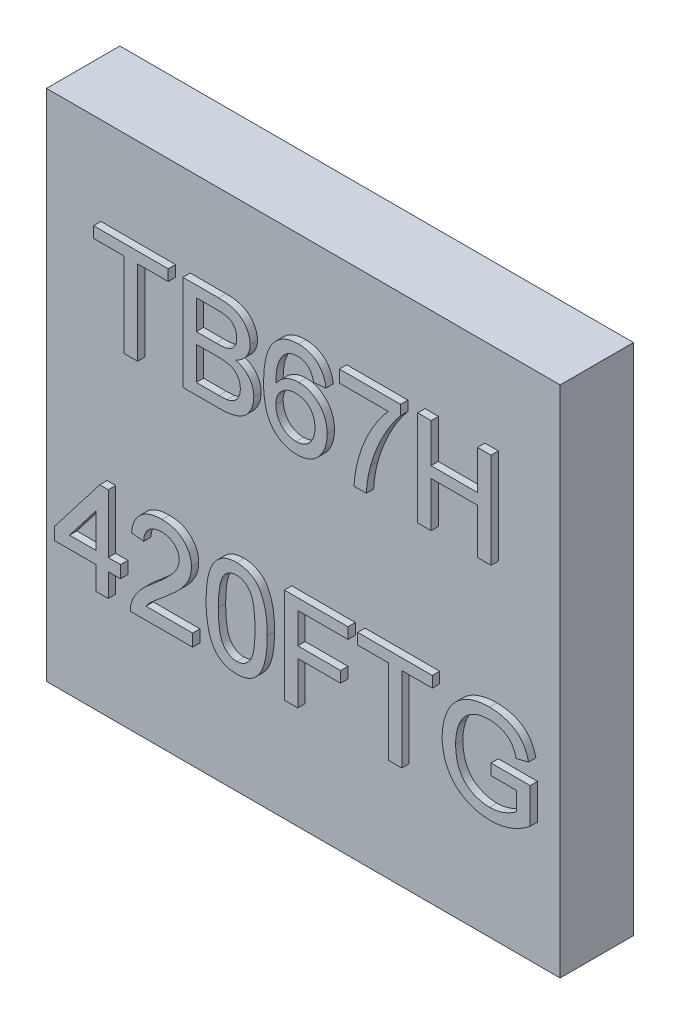
SolidWorks part; units mm, degrees
material "ABS"
ref_plane "Front Plane" through (0, 0, 0) normal (0, 0, 1) x (1, 0, 0)
ref_plane "Top Plane" through (0, 0, 0) normal (0, 1, 0) x (1, 0, 0)
ref_plane "Right Plane" through (0, 0, 0) normal (1, 0, 0) x (0, 0, -1)
sketch "Sketch1" plane through (0, 0, 0) normal (0, 0, 1) x (1, 0, 0)
  line L1 (-3.5, 3.5) -> (3.5, 3.5)
  line L2 (-3.5, 3.5) -> (-3.5, -3.5)
  line L3 (-3.5, -3.5) -> (3.5, -3.5)
  line L4 (3.5, 3.5) -> (3.5, -3.5)
  line L5 (-3.5, 3.5) -> (3.5, -3.5) construction
  line L6 (-3.5, -3.5) -> (3.5, 3.5) construction
  point P0 (0, 0)
  dimension "D1" = 7
  dimension "D2" = 7
extrude "Boss-Extrude1" add sketch "Sketch1" along normal blind 1
sketch "Sketch2" plane through (0, 0, 1) normal (0, 0, 1) x (1, 0, 0)
  line L0 (0, 0) -> (3.5, 0) construction
  line L1 (3.5, -3.5) -> (3.5, 3.5) construction
  line L2 (-3.5, 1) -> (3.5, 1) construction
  line L3 (-3.5, 3.5) -> (-3.5, -3.5) construction
  text T0 "TB67H\r\n420FTG" font "Arial" height 1.3
  dimension "D1" = 1
extrude "Boss-Extrude2" add sketch "Sketch2" along normal blind 0.1
